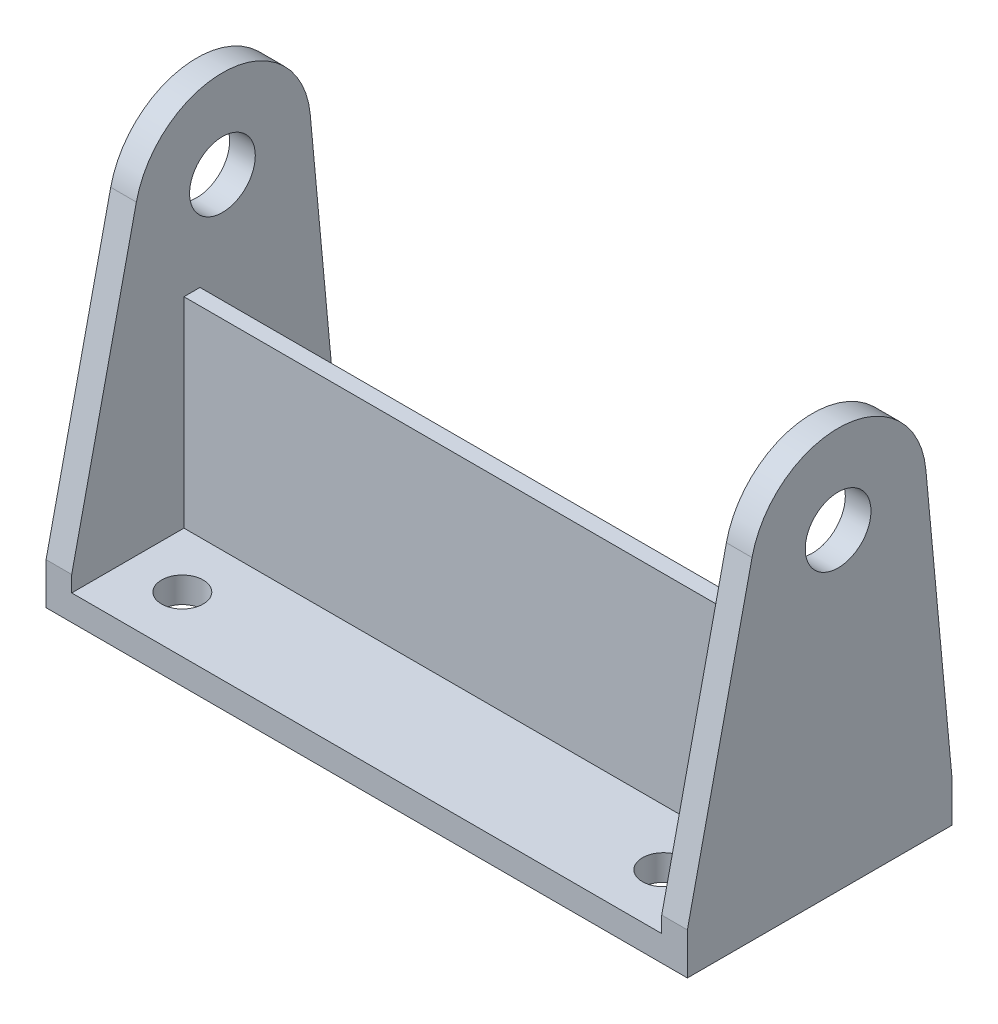
SolidWorks part; units mm, degrees
ref_plane "前视基准面" through (0, 0, 0) normal (0, 0, 1) x (1, 0, 0)
ref_plane "上视基准面" through (0, 0, 0) normal (0, 1, 0) x (1, 0, 0)
ref_plane "右视基准面" through (0, 0, 0) normal (1, 0, 0) x (0, 0, -1)
sketch "草图1" plane through (0, 0, 0) normal (0, 1, 0) x (1, 0, 0)
  line L1 (0, 0) -> (400, 0)
  line L2 (0, 0) -> (0, 165)
  line L3 (0, 165) -> (400, 165)
  line L4 (400, 0) -> (400, 165)
  circle A0 centre (350, 115) radius 13
  circle A1 centre (50, 115) radius 13
  circle A2 centre (50, 35) radius 13
  circle A3 centre (350, 35) radius 13
  dimension "D3" = 26
  dimension "D1" = 400
  dimension "D2" = 165
  dimension "D4" = 50
  dimension "D5" = 50
  dimension "D6" = 50
  dimension "D7" = 80
extrude "凸台-拉伸1" add sketch "草图1" along normal blind 16
sketch "草图2" plane through (0, 16, 0) normal (0, 1, 0) x (1, 0, 0)
  line L0 (400, 165) -> (0, 165) construction
  line L1 (16, 80) -> (384, 80)
  line L2 (16, 80) -> (16, 70)
  line L3 (16, 70) -> (384, 70)
  line L4 (384, 80) -> (384, 70)
  line L5 (0, 165) -> (0, 0) construction
  line L6 (400, 0) -> (400, 165) construction
  dimension "D1" = 85
  dimension "D2" = 10
  dimension "D3" = 16
  dimension "D4" = 16
extrude "凸台-拉伸2" add sketch "草图2" along normal blind 125
sketch "草图3" plane through (384, 0, 0) normal (1, 0, 0) x (0, 0, -1)
  line L0 (0, 0) -> (165, 0) construction
  line L1 (165, 16) -> (165, 0) construction
  line L2 (165, 16) -> (165, 26)
  line L3 (165, 16) -> (0, 16)
  line L4 (0, 16) -> (0, 26)
  line L5 (40.3162, 206.9602) -> (0, 26)
  line L6 (165, 26) -> (148.7624, 200.1073)
  circle A0 centre (94, 195) radius 20.5
  arc A1 (40.3162, 206.9602) -> (148.7624, 200.1073) centre (94, 195) cw
  dimension "D1" = 41
  dimension "D5" = 55
  dimension "D2" = 195
  dimension "D3" = 71
  dimension "D4" = 10
extrude "凸台-拉伸3" add sketch "草图3" along normal blind 16
ref_plane "基准面1" through (200, 0, 0) normal (1, 0, 0) x (0, 0, -1)
mirror "镜向1" about plane through (200, 0, 0) normal (1, 0, 0) of "凸台-拉伸3"
